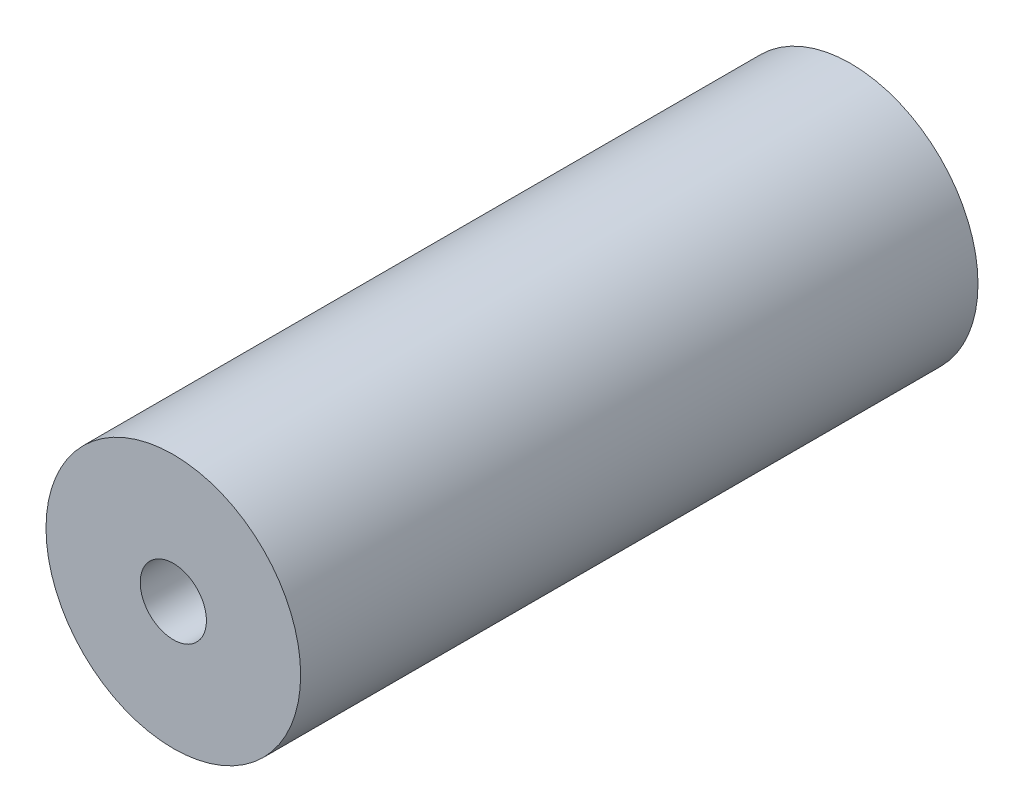
SolidWorks part; units mm, degrees
material "1060 合金"
ref_plane "正面" through (0, 0, 0) normal (0, 0, 1) x (1, 0, 0)
ref_plane "平面" through (0, 0, 0) normal (0, 1, 0) x (1, 0, 0)
ref_plane "右側面" through (0, 0, 0) normal (1, 0, 0) x (0, 0, -1)
sketch "ｽｹｯﾁ1" plane through (0, 0, 0) normal (0, 0, 1) x (1, 0, 0)
  circle A0 centre (0, 0) radius 1.3
  circle A1 centre (0, 0) radius 5
  dimension "D1" = 2.6
  dimension "D2" = 10
extrude "ﾎﾞｽ - 押し出し1" add sketch "ｽｹｯﾁ1" along normal blind 26.6
